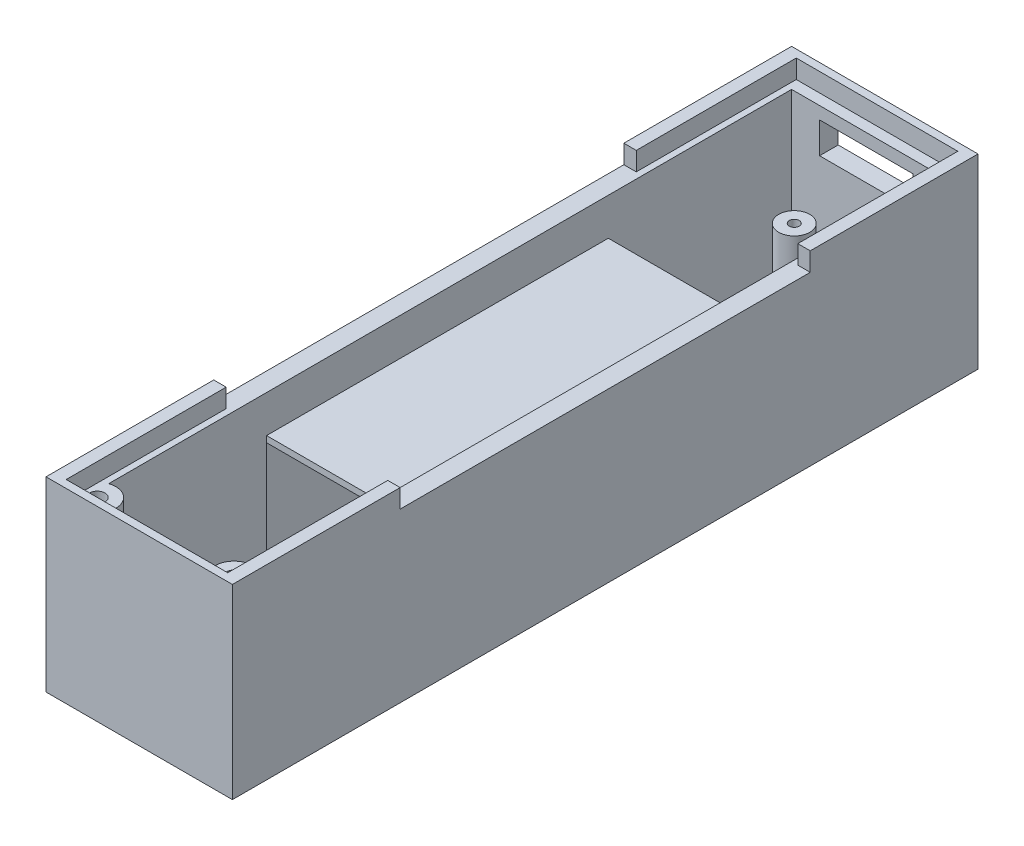
SolidWorks part; units mm, degrees
ref_plane "Front" through (0, 0, 0) normal (0, 0, 1) x (1, 0, 0)
ref_plane "Top" through (0, 0, 0) normal (0, 1, 0) x (1, 0, 0)
ref_plane "Right" through (0, 0, 0) normal (1, 0, 0) x (0, 0, -1)
sketch "Sketch1" plane through (0, 0, 0) normal (0, 1, 0) x (1, 0, 0)
  line L1 (-15, -60) -> (15, -60)
  line L2 (-15, -60) -> (-15, 60)
  line L3 (-15, 60) -> (15, 60)
  line L4 (15, -60) -> (15, 60)
  line L5 (-15, -60) -> (15, 60) construction
  line L6 (-15, 60) -> (15, -60) construction
  point P0 (0, 0)
  dimension "D1" = 120
  dimension "D2" = 30
extrude "Boss-Extrude1" add sketch "Sketch1" along normal blind 30 contours L2 L3 L4 L1
sketch "Sketch3" plane through (0, 30, 0) normal (0, 1, 0) x (1, 0, 0)
  line L1 (-12, -57) -> (12, -57)
  line L2 (-12, -57) -> (-12, 57)
  line L3 (-12, 57) -> (12, 57)
  line L4 (12, -57) -> (12, 57)
  line L5 (-12, -57) -> (12, 57) construction
  line L6 (-12, 57) -> (12, -57) construction
  point P0 (0, 0)
  dimension "D1" = 114
  dimension "D2" = 24
extrude "Cut-Extrude1" cut sketch "Sketch3" against normal blind 27.5
sketch "Sketch4" plane through (0, 30, 0) normal (0, 1, 0) x (1, 0, 0)
  line L1 (-13, -58.75) -> (13, -58.75)
  line L2 (-13, -58.75) -> (-13, 58.75)
  line L3 (-13, 58.75) -> (13, 58.75)
  line L4 (13, -58.75) -> (13, 58.75)
  line L5 (-13, -58.75) -> (13, 58.75) construction
  line L6 (-13, 58.75) -> (13, -58.75) construction
  point P0 (0, 0)
  dimension "D1" = 26
  dimension "D2" = 117.5
extrude "Cut-Extrude2" cut sketch "Sketch4" against normal blind 3
sketch "Sketch5" plane through (15, 0, 0) normal (1, 0, 0) x (0, 0, -1)
  line L0 (-60, 30) -> (60, 30) construction
  line L1 (-33, 27) -> (33, 27)
  line L2 (-33, 27) -> (-33, 30)
  line L3 (-33, 30) -> (33, 30)
  line L4 (33, 27) -> (33, 30)
  line L5 (-33, 27) -> (33, 30) construction
  line L6 (-33, 30) -> (33, 27) construction
  line L7 (0, 28.5) -> (0, 0) construction
  point P0 (0, 28.5)
  dimension "D1" = 66
  dimension "D2" = 3
extrude "Cut-Extrude3" cut sketch "Sketch5" against normal through all
sketch "Sketch6" plane through (0, 0, 0) normal (0, -1, 0) x (1, 0, 0)
  line L1 (-12.5, -27.5) -> (12.5, -27.5)
  line L2 (-12.5, -27.5) -> (-12.5, 27.5)
  line L3 (-12.5, 27.5) -> (12.5, 27.5)
  line L4 (12.5, -27.5) -> (12.5, 27.5)
  line L5 (-12.5, -27.5) -> (12.5, 27.5) construction
  line L6 (-12.5, 27.5) -> (12.5, -27.5) construction
  point P0 (0, 0)
  dimension "D1" = 25
  dimension "D2" = 55
extrude "Cut-Extrude4" cut sketch "Sketch6" against normal blind 20
sketch "Sketch8" plane through (0, 20, 0) normal (0, -1, 0) x (1, 0, 0)
  line L1 (12, 27.5) -> (-12, 27.5)
  line L2 (12, 27.5) -> (12, -27.5)
  line L3 (12, -27.5) -> (-12, -27.5)
  line L4 (-12, 27.5) -> (-12, -27.5)
  line L5 (12, 27.5) -> (-12, -27.5) construction
  line L6 (12, -27.5) -> (-12, 27.5) construction
  point P0 (0, 0)
extrude "Boss-Extrude2" add sketch "Sketch8" against normal blind 1
sketch "Sketch9" plane through (0, 0, -60) normal (0, 0, -1) x (-1, 0, 0)
  line L0 (0, 0) -> (0, 30) construction
  line L1 (7.5, 25) -> (-7.5, 25)
  line L2 (7.5, 25) -> (7.5, 20)
  line L3 (7.5, 20) -> (-7.5, 20)
  line L4 (-7.5, 25) -> (-7.5, 20)
  line L5 (7.5, 25) -> (-7.5, 20) construction
  line L6 (7.5, 20) -> (-7.5, 25) construction
  line L7 (15, 0) -> (-15, 0) construction
  line L8 (15, 30) -> (-15, 30) construction
  point P0 (0, 22.5)
  dimension "D1" = 5
  dimension "D2" = 15
  dimension "D3" = 5
extrude "Cut-Extrude5" cut sketch "Sketch9" against normal up to surface (3 mm away) up to face at (0, 14.75, -57)
sketch "Sketch10" plane through (0, 2.5, 0) normal (0, 1, 0) x (1, 0, 0)
  line L0 (0, 0) -> (0, 57) construction
  line L1 (12, 57) -> (-12, 57) construction
  line L2 (-12, 42.25) -> (12, 42.25) construction
  line L3 (-12, 57) -> (-12, 27.5) construction
  line L4 (12, 27.5) -> (12, 57) construction
  circle A0 centre (-7.62, 31.455) radius 2.5
  circle A1 centre (-7.62, 53.045) radius 2.5
  circle A2 centre (7.62, 53.045) radius 2.5
  circle A3 centre (7.62, 31.455) radius 2.5
  point P13 (-7.62, 53.045)
  point P16 (7.62, 31.455)
  point P17 (7.62, 53.045)
  dimension "D2" = 5
  dimension "D1" = 21.59
  dimension "D3" = 15.24
extrude "Boss-Extrude3" add sketch "Sketch10" along normal blind 10
sketch "Sketch13" plane through (0, 27, 0) normal (0, 1, 0) x (1, 0, 0)
  line L0 (0, -57) -> (0, -37.9781) construction
  line L1 (-12, -57) -> (12, -57) construction
  line L2 (-12, -27.5) -> (-12, -57) construction
  line L3 (-12, -57) -> (12, -57) construction
  line L5 (-12, -52.9216) -> (-12, -57)
  line L6 (-12, -57) -> (-8.2728, -57)
  line L7 (12, -57) -> (8.2728, -57)
  line L8 (12, -52.9216) -> (12, -57)
  line L9 (-13, -33) -> (-13, -58.75) construction
  line L10 (-13, -58.75) -> (13, -58.75) construction
  arc A0 (-12, -52.9216) -> (-8.2728, -57) centre (-11, -55.75) cw
  arc A1 (12, -52.9216) -> (8.2728, -57) centre (11, -55.75) ccw
  dimension "D1" = 3
  dimension "D2" = 2
  dimension "D3" = 3
extrude "Boss-Extrude4" add sketch "Sketch13" against normal up to surface (24.5 mm away) up to face at (0, 2.5, 42.25)
hole_wizard "M2x0.4 Tapped Hole1" positions "Sketch11" profile "Sketch12" tap size "M2x0.4" standard "ANSI Metric"
sketch "Sketch11" plane through (0, 12.5, 0) normal (0, 1, 0) x (1, 0, 0)
  point P0 (-7.62, 31.455)
  point P3 (-7.62, 53.045)
  point P6 (7.62, 53.045)
  point P9 (7.62, 31.455)
sketch "Sketch12" plane through (-7.62, 12.5, -31.455) normal (1, 0, 0) x (0, 0, 1)
  line L0 (0, 0) -> (0, 5.6807)
  line L1 (0, 5.6807) -> (0.8, 5.2)
  line L2 (0.8, 5.2) -> (0.8, 0)
  line L5 (0.8, 0) -> (0, 0)
  line L10 (0, 5.6807) -> (-0.8, 5.2) construction
  line L11 (0, -6.35) -> (0, 107.95) construction
  dimension "Tap Drill Dia." = 1.6
  dimension "Tap Drill Depth" = 5.2
  dimension "Drill Angle" = 118
cosmetic thread "Hole Thread1" parameters "D1"=4, "D2"=2
cosmetic thread "Hole Thread2" parameters "D1"=4, "D2"=2
cosmetic thread "Hole Thread3" parameters "D1"=4, "D2"=2
cosmetic thread "Hole Thread4" parameters "D1"=4, "D2"=2
hole_wizard "Tap Drill for M3x0.5 Tap2" positions "Sketch18" profile "Sketch19" hole size "M3x0.5" standard "ANSI Metric" end condition through all
sketch "Sketch18" plane through (0, 27, 0) normal (0, 1, 0) x (1, 0, 0)
  point P0 (-11, -55.75)
  point P3 (11, -55.75)
sketch "Sketch19" plane through (-11, 27, 55.75) normal (1, 0, 0) x (0, 0, 1)
  line L0 (0, 0) -> (0, 27)
  line L1 (0, 27) -> (1.25, 27)
  line L2 (1.25, 27) -> (1.25, 0)
  line L5 (1.25, 0) -> (0, 0)
  line L11 (0, -6.35) -> (0, 107.95) construction
  dimension "Thru Hole Dia." = 2.5
  dimension "Thru Hole Depth" = 27
sketch "Sketch22" plane through (0, 2.5, 0) normal (0, 1, 0) x (1, 0, 0)
  line L0 (-8.2728, -57) -> (8.2728, -57) construction
  line L1 (-4, -57) -> (4, -57)
  line L2 (-4, -57) -> (-4, -42)
  line L3 (-4, -42) -> (4, -42)
  line L4 (4, -57) -> (4, -42)
  line L5 (-4, -57) -> (4, -42) construction
  line L6 (-4, -42) -> (4, -57) construction
  line L7 (0, -49.5) -> (0, -57) construction
  point P0 (0, -49.5)
  dimension "D1" = 8
  dimension "D2" = 15
extrude "Cut-Extrude6" cut sketch "Sketch22" against normal through all
